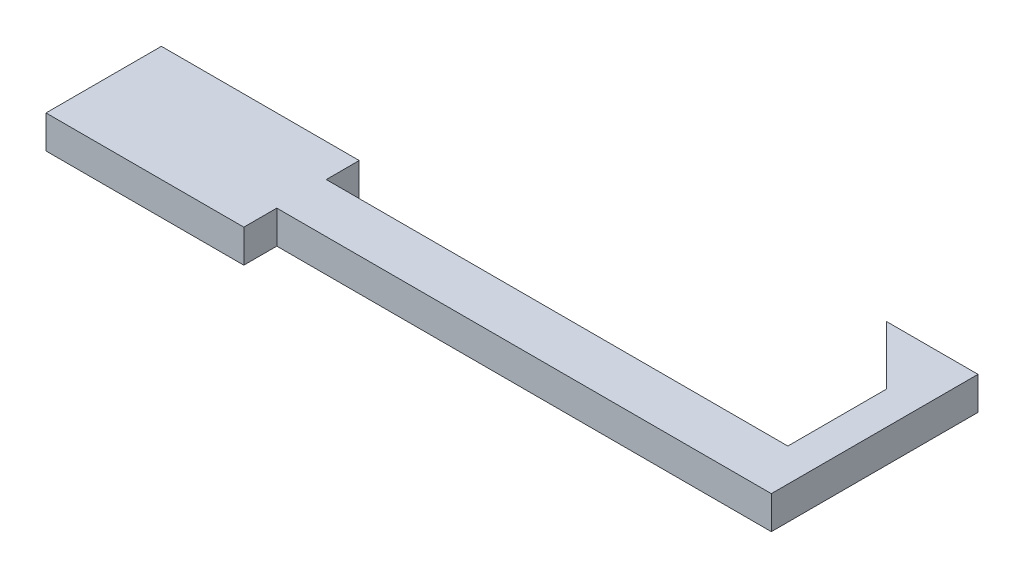
SolidWorks part; units mm, degrees
ref_plane "Front Plane" through (0, 0, 0) normal (0, 0, 1) x (1, 0, 0)
ref_plane "Top Plane" through (0, 0, 0) normal (0, 1, 0) x (1, 0, 0)
ref_plane "Right Plane" through (0, 0, 0) normal (1, 0, 0) x (0, 0, -1)
sketch "Sketch1" plane through (0, 0, 0) normal (0, 1, 0) x (1, 0, 0)
  line L0 (-27.9733, 22.1922) -> (-20.9733, 22.1922)
  line L1 (-20.9733, 22.1922) -> (-20.9733, 23.6922)
  line L2 (-20.9733, 23.6922) -> (-21.8572, 24.5761)
  line L3 (-21.8572, 24.5761) -> (-20.4733, 24.5761)
  line L4 (-20.4733, 24.5761) -> (-20.4733, 21.4422)
  line L5 (-27.9733, 22.1922) -> (-27.9733, 21.4422)
  line L6 (-27.9733, 21.4422) -> (-20.4733, 21.4422)
  line L7 (-27.9733, 22.1922) -> (-27.9733, 22.6922)
  line L8 (-27.9733, 22.6922) -> (-30.9733, 22.6922)
  line L9 (-27.9733, 21.4422) -> (-27.9733, 20.9422)
  line L10 (-27.9733, 20.9422) -> (-30.9733, 20.9422)
  line L11 (-30.9733, 20.9422) -> (-30.9733, 22.6922)
extrude "Boss-Extrude1" add sketch "Sketch1" along normal blind 0.5 contours L11 L10 L9 L5 L7 L8 | L5 L6 L4 L3 L2 L1 L0
